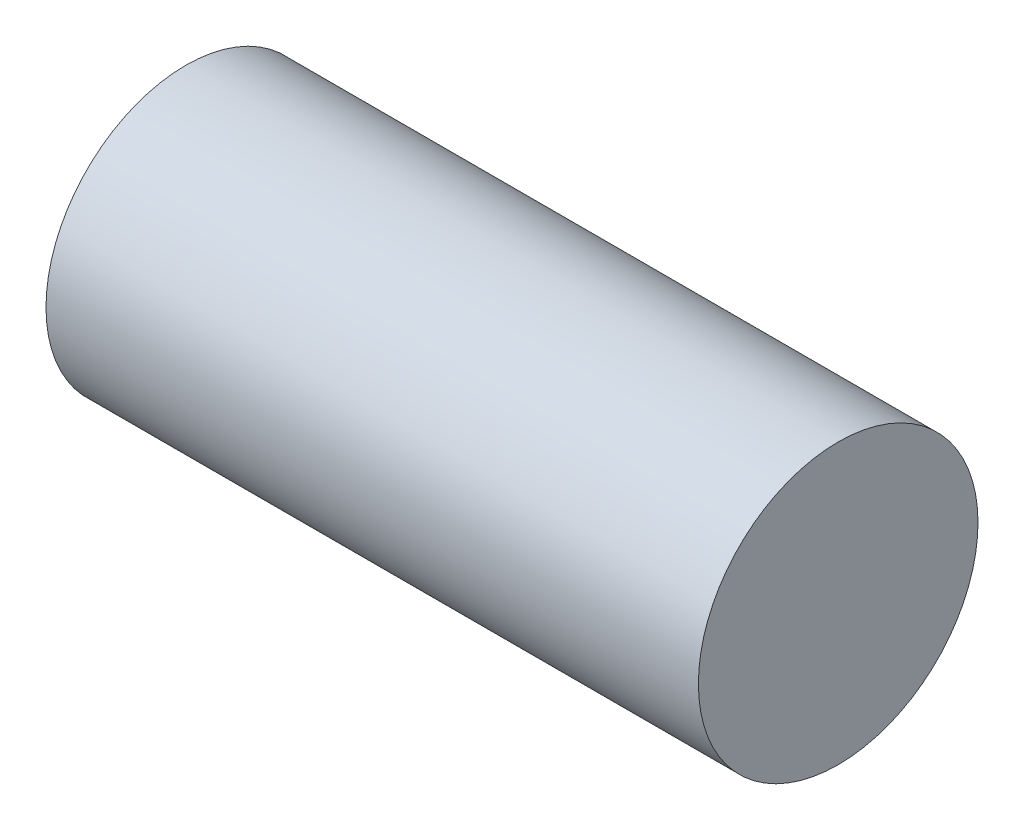
SolidWorks part; units mm, degrees
material "AISI 4340 Steel, normalized"
ref_plane "Front Plane" through (0, 0, 0) normal (0, 0, 1) x (1, 0, 0)
ref_plane "Top Plane" through (0, 0, 0) normal (0, 1, 0) x (1, 0, 0)
ref_plane "Right Plane" through (0, 0, 0) normal (1, 0, 0) x (0, 0, -1)
sketch "Sketch1" plane through (0, 0, 0) normal (1, 0, 0) x (0, 0, -1)
  circle A0 centre (0, 0) radius 38.1
  dimension "D1" = 76.2
extrude "Boss-Extrude1" add sketch "Sketch1" along normal blind 177.8
scale "Scale1" scale about centroid uniform scaling yes scale factor 2.84
